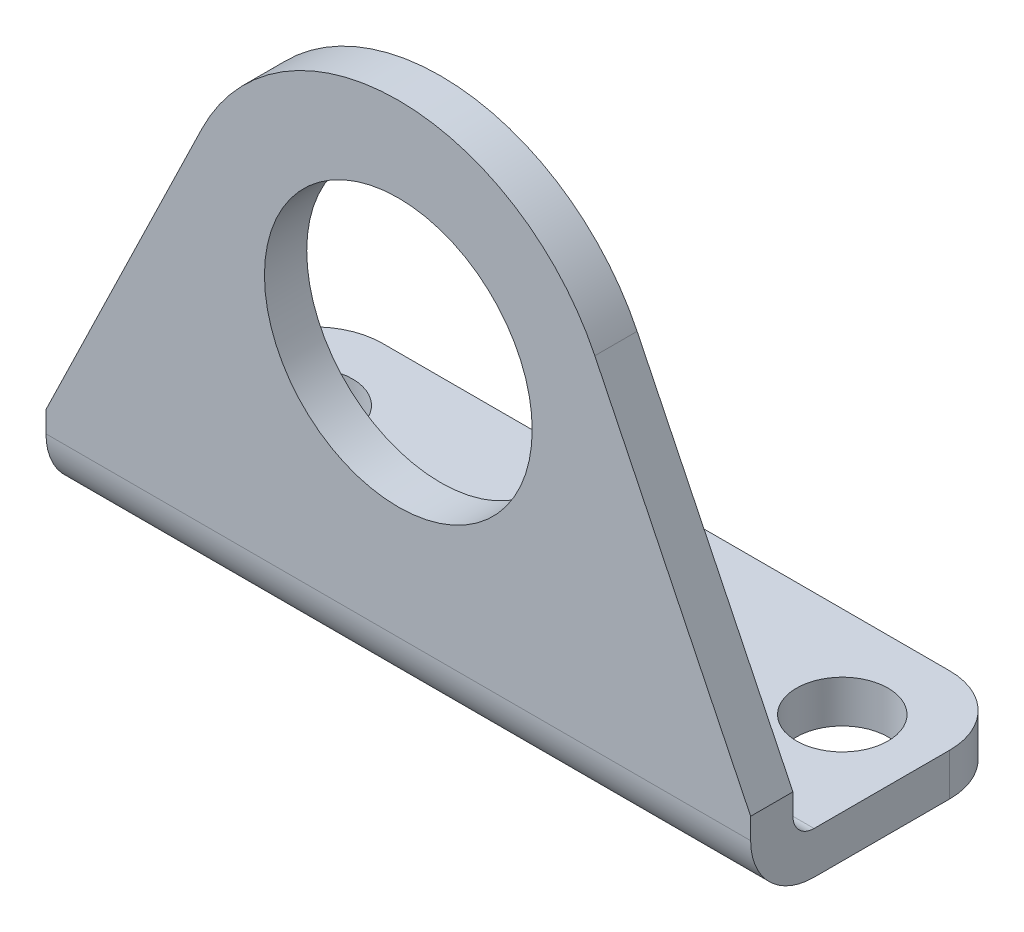
SolidWorks part; units mm, degrees
ref_plane "Front Plane" through (0, 0, 0) normal (0, 0, 1) x (1, 0, 0)
ref_plane "Top Plane" through (0, 0, 0) normal (0, 1, 0) x (1, 0, 0)
ref_plane "Right Plane" through (0, 0, 0) normal (1, 0, 0) x (0, 0, -1)
sketch "Sketch1" plane through (0, 0, 0) normal (0, 1, 0) x (1, 0, 0)
  line L0 (-12.7, 0) -> (12.7, 0) construction
  line L1 (0, 3.302) -> (0, -6.35) construction
  circle A2 centre (-9.652, 0) radius 1.651
  circle A3 centre (9.652, 0) radius 1.651
  point P6 (12.7, 3.302)
  point P9 (12.7, -6.35)
  point P10 (-12.7, -6.35)
  point P11 (-12.7, 3.302)
  point P13 (9.652, 1.651)
  point P21 (9.652, -1.651)
  dimension "Mounting Slot Width" = 3.302
  dimension "Overall Length" = 25.4
  dimension "Depth" = 9.652
  dimension "Hole Location" = 9.652
  dimension "D5" = 9.652
  dimension "HL" = 6.35
sketch "Sketch2" plane through (0, 0, 0) normal (0, 0, 1) x (1, 0, 0)
  line L0 (-12.7, 0) -> (12.7, 0)
  line L1 (12.7, 0) -> (12.7, 3.048)
  line L2 (12.7, 3.048) -> (7.0831, 14.6154)
  line L3 (-12.7, 0) -> (-12.7, 3.048)
  line L4 (-12.7, 3.048) -> (-7.0831, 14.6154)
  line L5 (0, 0) -> (0, 11.176) construction
  line L6 (-12.7, 1.524) -> (12.7, 1.524) construction
  arc A0 (-7.0831, 14.6154) -> (7.0831, 14.6154) centre (0, 11.176) cw
  circle A1 centre (0, 11.176) radius 4.826
  point P13 (0, 19.05)
  point P15 (4.826, 11.176)
  point P16 (-4.826, 11.176)
  dimension "ID" = 9.652
  dimension "Radius" = 7.874
  dimension "C to C" = 11.176
  dimension "Height" = 19.05
  dimension "Base Plate Thickness" = 1.524
  dimension "D5" = 3.048
sketch "Sketch3" plane through (0, 0, 0) normal (0, 0, 1) x (1, 0, 0)
  line L5 (-12.7, 0) -> (12.7, 0)
  line L6 (12.7, 0) -> (12.7, 3.048)
  line L7 (12.7, 3.048) -> (7.0831, 14.6154)
  line L8 (-7.0831, 14.6154) -> (-12.7, 3.048)
  line L9 (-12.7, 3.048) -> (-12.7, 0)
  line L10 (-12.7, 0) -> (12.7, 0)
  line L11 (12.7, 0) -> (12.7, 3.048)
  line L12 (12.7, 3.048) -> (7.0831, 14.6154)
  line L13 (-7.0831, 14.6154) -> (-12.7, 3.048)
  line L14 (-12.7, 3.048) -> (-12.7, 0)
  circle A1 centre (0, 11.176) radius 4.826
  circle A2 centre (0, 11.176) radius 4.826
  arc A3 (7.0831, 14.6154) -> (-7.0831, 14.6154) centre (0, 11.176) ccw
  arc A4 (7.0831, 14.6154) -> (-7.0831, 14.6154) centre (0, 11.176) ccw
  dimension "D1" = 0
  dimension "D2" = 0
extrude "Boss-Extrude1" add sketch "Sketch3" along normal up to vertex (6.35 mm away) and the other way up to vertex (3.302 mm away) up to point (0, 0, 6.35) other way up to point (0, 0, -3.302)
sketch "Sketch4" plane through (0, 0, 0) normal (0, 1, 0) x (1, 0, 0)
  circle A2 centre (9.652, 0) radius 1.651 construction
  circle A3 centre (-9.652, 0) radius 1.651 construction
  circle A4 centre (9.652, 0) radius 1.651
  circle A5 centre (-9.652, 0) radius 1.651
extrude "Cut-Extrude1" cut sketch "Sketch4" along normal through all
sketch "Sketch5" plane through (-12.7, 0, 0) normal (-1, 0, 0) x (0, 0, 1)
  line L0 (6.35, 14.6154) -> (6.35, 3.048) construction
  line L1 (-3.302, 19.05) -> (4.826, 19.05)
  line L2 (-3.302, 19.05) -> (-3.302, 1.524)
  line L3 (-3.302, 1.524) -> (4.064, 1.524)
  line L4 (4.826, 19.05) -> (4.826, 2.286)
  line L5 (-3.302, 3.048) -> (-3.302, 0) construction
  line L6 (6.35, 19.05) -> (-3.302, 19.05) construction
  line L7 (-3.302, 0) -> (6.35, 0) construction
  line L8 (6.35, 3.048) -> (6.35, 0) construction
  line L9 (4.064, 0) -> (6.35, 0)
  line L10 (6.35, 2.286) -> (6.35, 0)
  arc A0 (4.064, 1.524) -> (4.826, 2.286) centre (4.064, 2.286) ccw
  arc A1 (4.064, 0) -> (6.35, 2.286) centre (4.064, 2.286) ccw
  dimension "D3" = 0.762
  dimension "D4" = 2.286
  dimension "D1" = 1.524
  dimension "Thickness" = 1.524
extrude "Cut-Extrude2" cut sketch "Sketch5" against normal through all
fillet "Fillet1" radius 2.4765 2 edges at (-12.7, 0.762, -3.302) (12.7, 0.762, -3.302)
equation "\"D4@Sketch5\" = \"D1@Sketch5\"+\"D3@Sketch5\""
equation "\"D3@Sketch5\" = \"Thickness@Sketch5\"/2"
equation "\"D1@Fillet1\" = \"Mounting Slot Width@Sketch1\" * .750"
equation "\"Thickness@Sketch5\" = \"Base Plate Thickness@Sketch2\""
equation "\"D1@Sketch5\" = \"Thickness@Sketch5\""
equation "\"D5@Sketch1\"=\"Hole Location@Sketch1\""
